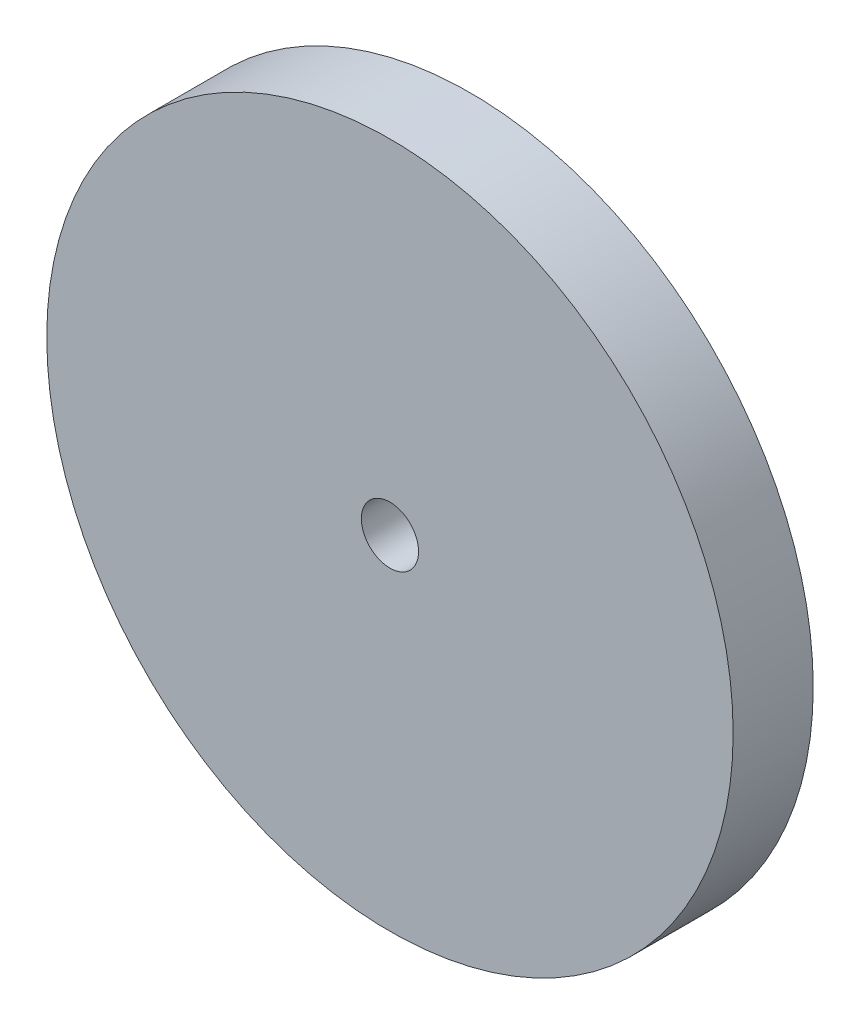
SolidWorks part; units mm, degrees
ref_plane "Спереди" through (0, 0, 0) normal (0, 0, 1) x (1, 0, 0)
ref_plane "Сверху" through (0, 0, 0) normal (0, 1, 0) x (1, 0, 0)
ref_plane "Справа" through (0, 0, 0) normal (1, 0, 0) x (0, 0, -1)
sketch "Эскиз1" plane through (0, 0, 0) normal (0, 0, 1) x (1, 0, 0)
  circle A0 centre (0, 0) radius 2.5
  circle A1 centre (0, 0) radius 30
  dimension "D1" = 5
  dimension "D2" = 60
extrude "Бобышка-Вытянуть2" add sketch "Эскиз1" against normal blind 7 separate body
